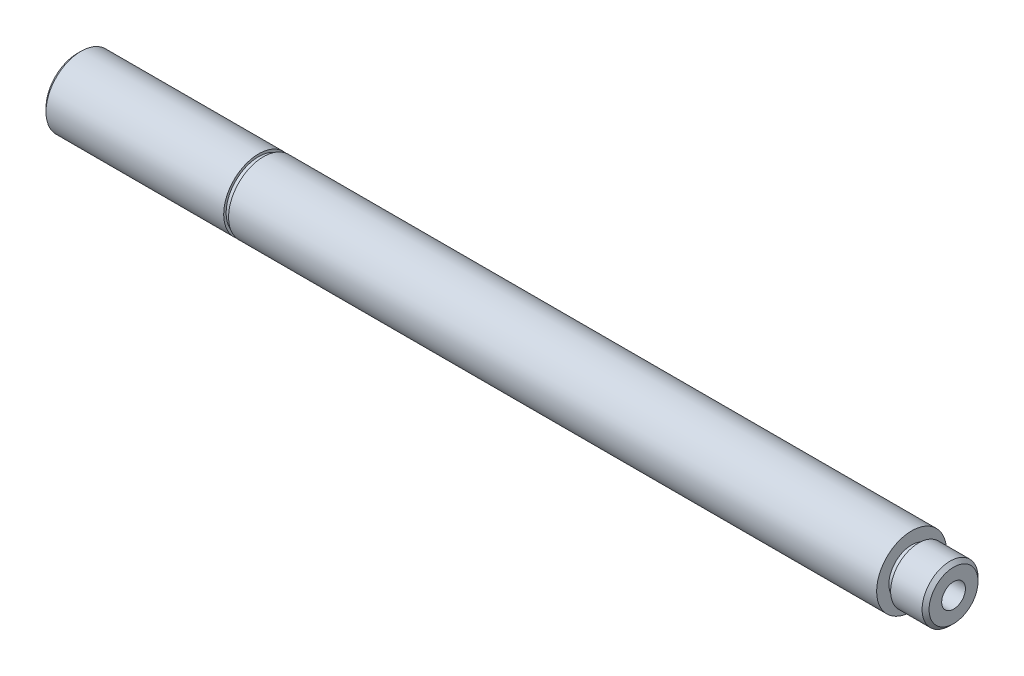
SolidWorks part; units mm, degrees
material "1.7033 (34Cr4)"
ref_plane "Спереди" through (0, 0, 0) normal (0, 0, 1) x (1, 0, 0)
ref_plane "Сверху" through (0, 0, 0) normal (0, 1, 0) x (1, 0, 0)
ref_plane "Справа" through (0, 0, 0) normal (1, 0, 0) x (0, 0, -1)
sketch "Эскиз1" plane through (0, 0, 0) normal (0, 0, 1) x (1, 0, 0)
  line L1 (0, 10) -> (238.5, 10)
  line L2 (250.5, 8) -> (250.5, 0)
  line L5 (250.5, 0) -> (0, 0)
  line L9 (-123.3359, 0) -> (701.1337, 0) construction
  line L16 (238.5, 10) -> (238.5, 8)
  line L17 (238.5, 8) -> (250.5, 8)
  line L22 (0, 0) -> (0, 10)
  dimension "D2" = 20
  dimension "D4" = 250.5
  dimension "D5" = 12
  dimension "D6" = 16
revolve "Повернуть1" add sketch "Эскиз1" angle 360 about L9
hole_wizard "Отверстие обработанное метчиком M10x1.52" positions "Эскиз4" profile "Эскиз5" tap size "M10x1.5" standard "Ansi Metric"
sketch "Эскиз4" plane through (0, 0, 0) normal (-1, 0, 0) x (0, 0, 1)
  point P0 (0, 0)
sketch "Эскиз5" plane through (0, 0, 0) normal (0, 1, 0) x (0, 0, 1)
  line L0 (0, 0) -> (0, 40.0537)
  line L1 (0, 40.0537) -> (4.25, 37.5)
  line L2 (4.25, 37.5) -> (4.25, 1.25)
  line L3 (4.25, 1.25) -> (5.5, 0)
  line L5 (5.5, 0) -> (0, 0)
  line L6 (-4.25, 1.25) -> (-5.5, 0) construction
  line L10 (0, 40.0537) -> (-4.25, 37.5) construction
  line L11 (0, -6.35) -> (0, 107.95) construction
  dimension "Диаметр сверла" = 8.5
  dimension "Глубина сверла" = 37.5
  dimension "Диаметр передней зенковки" = 11
  dimension "Угол передней зенковки" = 90
  dimension "Угол заточки сверла" = 118
cosmetic thread "Отверстие резьбы2" parameters "D1"=30, "D2"=10
sketch "Эскиз19" plane through (250.5, 0, 0) normal (1, 0, 0) x (0, 0, -1)
  point P0 (0, 0)
hole_wizard "Отверстие обработанное метчиком M81" positions "Эскиз19" profile "Эскиз18" tap size "M8" standard "ISO"
cosmetic thread "Отверстие резьбы3" parameters "D1"=18.5, "D2"=8
sketch "Эскиз18" plane through (250.5, 0, 0) normal (0, 1, 0) x (0, 0, -1)
  line L0 (0, 0) -> (0, 22.0429)
  line L1 (0, 22.0429) -> (3.4, 20)
  line L2 (3.4, 20) -> (3.4, 0)
  line L5 (3.4, 0) -> (0, 0)
  line L10 (0, 22.0429) -> (-3.4, 20) construction
  line L11 (0, -6.35) -> (0, 107.95) construction
  dimension "Диаметр сверла" = 6.8
  dimension "Глубина сверла" = 20
  dimension "Угол заточки сверла" = 118
sketch "Эскиз6" plane through (0, 0, 0) normal (0, 0, 1) x (1, 0, 0)
  line L5 (0, 0) -> (50000, 0) construction
  line L8 (238.5, -10) -> (238.5, 10) construction
  line L9 (238.5, 8) -> (240.5, 8)
  line L10 (238.5, 8) -> (238.5, 6.5)
  line L11 (238.5, 6.5) -> (240.5, 6.5)
  line L12 (240.5, 8) -> (240.5, 6.5)
  dimension "D1" = 13
  dimension "D2" = 2
revolve "Вырез-Повернуть1" cut sketch "Эскиз6" angle 360 about L5
sketch "Эскиз20" plane through (0, 0, 0) normal (0, 0, 1) x (1, 0, 0)
  line L0 (238.5, 10) -> (0, 10) construction
  line L1 (51.8, 10) -> (53.2, 10)
  line L2 (51.8, 10) -> (51.8, 9.3)
  line L3 (51.8, 9.3) -> (53.2, 9.3)
  line L4 (53.2, 10) -> (53.2, 9.3)
  line L10 (0, 0) -> (50000, 0) construction
  line L11 (0, 10) -> (0, -10) construction
  dimension "D1" = 1.4
  dimension "D2" = 18.6
  dimension "D4" = 51.8
revolve "Вырез-Повернуть2" cut sketch "Эскиз20" angle 360 about L10
chamfer "Фаска1" distance 1 angle 45 2 edges at (250.5, 0, 8) (0, 0, 10)
